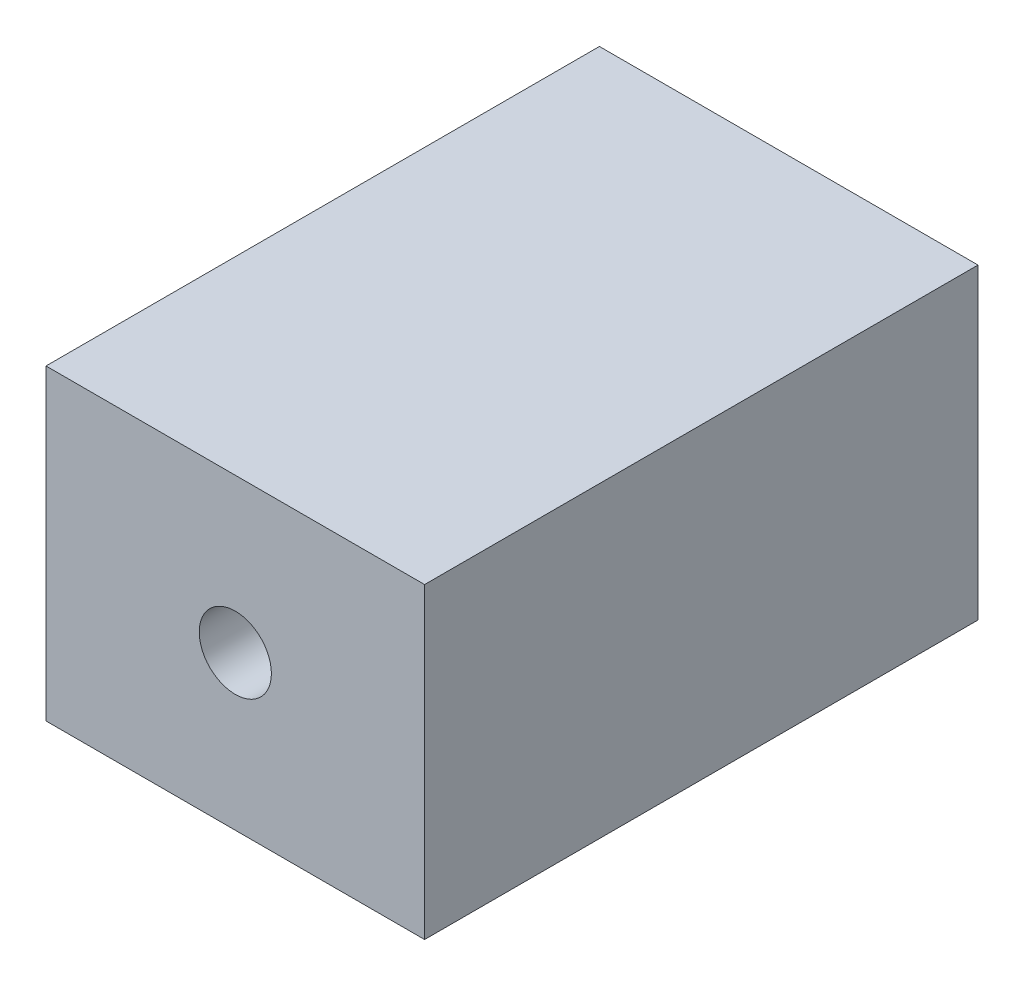
SolidWorks part; units mm, degrees
material "6061-T6 (SS)"
ref_plane "Front Plane" through (0, 0, 0) normal (0, 0, 1) x (1, 0, 0)
ref_plane "Top Plane" through (0, 0, 0) normal (0, 1, 0) x (1, 0, 0)
ref_plane "Right Plane" through (0, 0, 0) normal (1, 0, 0) x (0, 0, -1)
sketch "Sketch1" plane through (0, 0, 0) normal (0, 0, 1) x (1, 0, 0)
  line L1 (-37.25, -30.25) -> (37.25, -30.25)
  line L2 (-37.25, -30.25) -> (-37.25, 30.25)
  line L3 (-37.25, 30.25) -> (37.25, 30.25)
  line L4 (37.25, -30.25) -> (37.25, 30.25)
  circle A0 centre (0, 0) radius 7.1
extrude "Conservative_Manufacturer_Case_Envelope" add sketch "Sketch1" along normal blind 108.9
sketch "Sketch2" plane through (0, 0, 0) normal (0, 0, 1) x (1, 0, 0)
  circle A0 centre (0, 0) radius 25
  circle A1 centre (0, 0) radius 7.1
extrude "D50_Pilot_Envelope" add sketch "Sketch2" along normal blind 2 from offset 2
